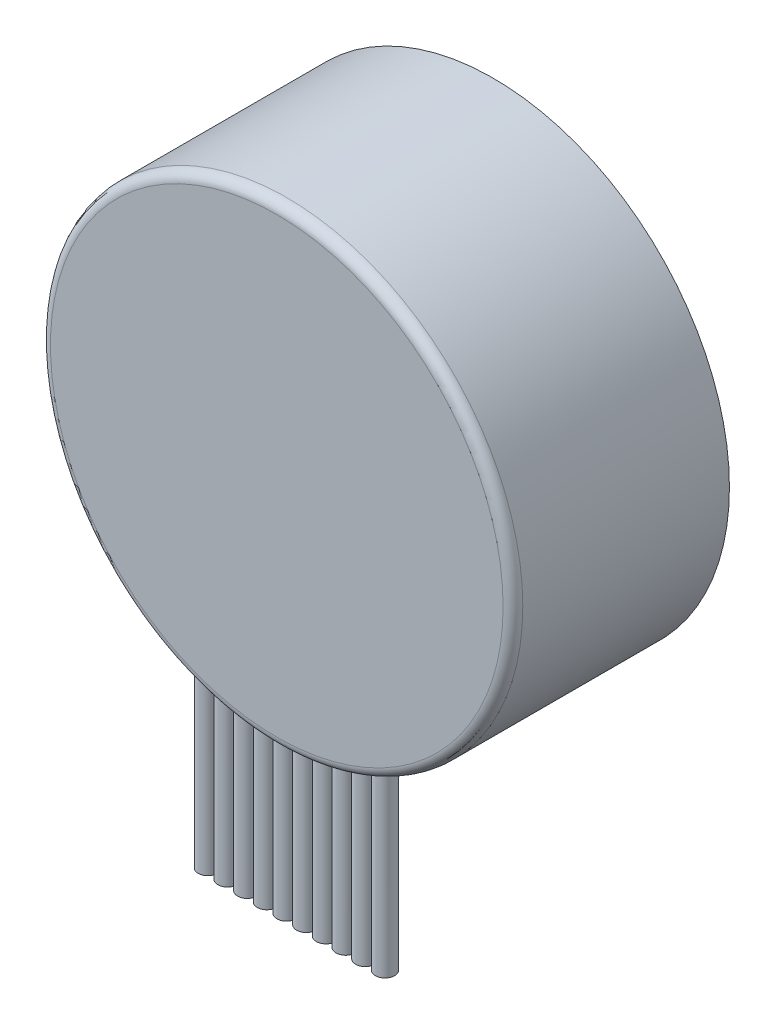
SolidWorks part; units mm, degrees
material "ABS"
ref_plane "Face" through (0, 0, 0) normal (0, 0, 1) x (1, 0, 0)
ref_plane "Dessus" through (0, 0, 0) normal (0, 1, 0) x (1, 0, 0)
ref_plane "Droite" through (0, 0, 0) normal (1, 0, 0) x (0, 0, -1)
sketch "Esquisse1" plane through (0, 0, 0) normal (0, 0, 1) x (1, 0, 0)
  circle A0 centre (0, 0) radius 12
  dimension "D1" = 24
extrude "Boss.-Extru.1" add sketch "Esquisse1" along normal blind 11
fillet "Congé1" radius 0.5 1 edges at (12, 0, 11)
sketch "Esquisse2" plane through (0, 0, 0) normal (0, 1, 0) x (1, 0, 0)
  circle A0 centre (0.5, -10) radius 0.49
  circle A1 centre (1.5, -10) radius 0.49
  circle A2 centre (2.5, -10) radius 0.49
  circle A3 centre (3.5, -10) radius 0.49
  circle A4 centre (4.5, -10) radius 0.49
  circle A5 centre (-0.5, -10) radius 0.49
  circle A6 centre (-1.5, -10) radius 0.49
  circle A7 centre (-2.5, -10) radius 0.49
  circle A8 centre (-3.5, -10) radius 0.49
  circle A9 centre (-4.5, -10) radius 0.49
extrude "Boss.-Extru.2" add sketch "Esquisse2" against normal blind 20
